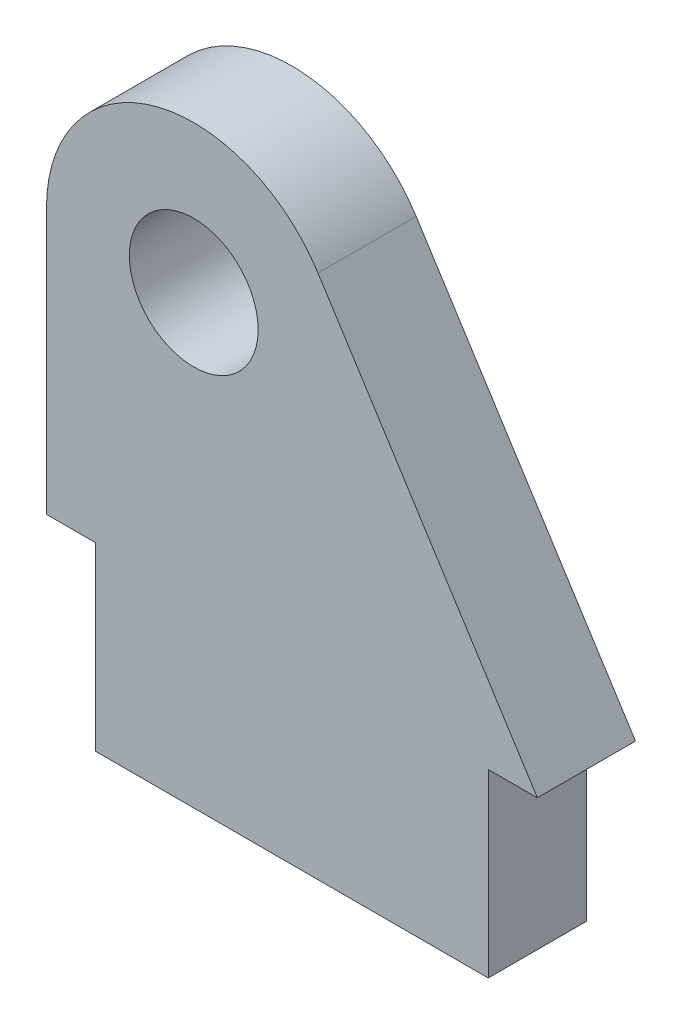
SolidWorks part; units mm, degrees
ref_plane "Front Plane" through (0, 0, 0) normal (0, 0, 1) x (1, 0, 0)
ref_plane "Top Plane" through (0, 0, 0) normal (0, 1, 0) x (1, 0, 0)
ref_plane "Right Plane" through (0, 0, 0) normal (1, 0, 0) x (0, 0, -1)
sketch "Sketch1" plane through (0, 0, 0) normal (0, 0, 1) x (1, 0, 0)
  line L0 (7.9375, 2.921) -> (0.8431, 14.0706)
  line L1 (6.35, -2.921) -> (-6.35, -2.921)
  line L2 (6.35, -2.921) -> (6.35, 2.921)
  line L3 (6.35, 2.921) -> (7.9375, 2.921)
  line L4 (-6.35, -2.921) -> (-6.35, 2.921)
  line L5 (6.35, -2.921) -> (-6.35, 2.921) construction
  line L6 (6.35, 2.921) -> (-6.35, -2.921) construction
  line L7 (-7.9375, 2.921) -> (-6.35, 2.921)
  line L8 (-7.9375, 2.921) -> (-7.9375, 11.5139)
  circle A0 centre (-3.175, 11.5139) radius 2.0828
  arc A1 (0.8431, 14.0706) -> (-7.9375, 11.5139) centre (-3.175, 11.5139) ccw
  point P0 (0, 0)
  dimension "D8" = 9.525
  dimension "D6" = 4.1656
  dimension "D1" = 12.7
  dimension "D2" = 5.842
  dimension "D3" = 8.5929
  dimension "D4" = 1.5875
  dimension "D5" = 1.5875
  dimension "D7" = 3.175
extrude "Boss-Extrude1" add sketch "Sketch1" along normal blind 3.175
